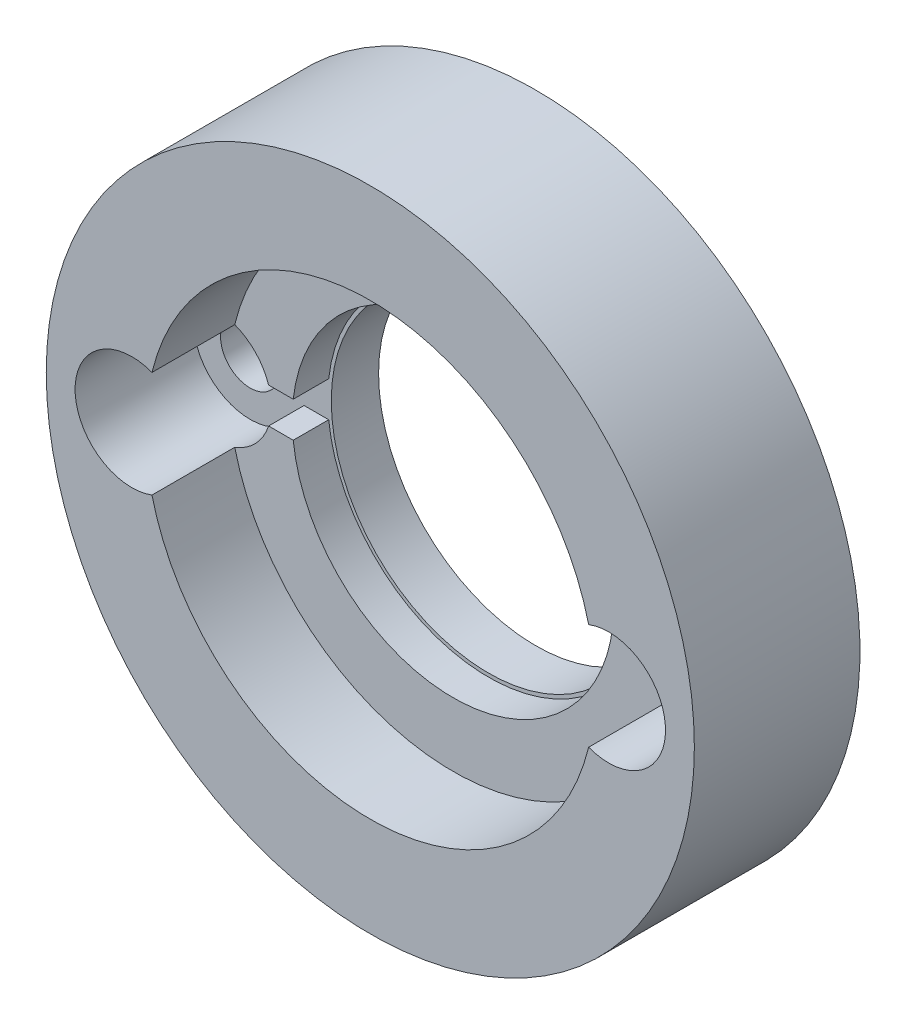
SolidWorks part; units mm, degrees
ref_plane "Alzado" through (0, 0, 0) normal (0, 0, 1) x (1, 0, 0)
ref_plane "Planta" through (0, 0, 0) normal (0, 1, 0) x (1, 0, 0)
ref_plane "Vista lateral" through (0, 0, 0) normal (1, 0, 0) x (0, 0, -1)
sketch "Croquis1" plane through (0, 0, 0) normal (0, 0, 1) x (1, 0, 0)
  line L0 (0, 8.3596) -> (0, -1.3417) construction
  line L1 (9, 0.75) -> (-9, 0.75)
  line L2 (0, 0.75) -> (0, -0.75)
  line L3 (9, -0.75) -> (-9, -0.75)
  line L4 (-9, 0.75) -> (-9, -0.75)
  line L5 (-12.48, 10.7299) -> (-12.48, -4.9079) construction
  line L6 (9, 0.75) -> (9, -0.75)
  line L7 (0, 0) -> (-17.6562, 0) construction
  circle A0 centre (-10.08, 0) radius 2.4
  circle A1 centre (-10.08, 0) radius 0.9
  circle A2 centre (10.08, 0) radius 0.9
  circle A3 centre (10.08, 0) radius 2.4
  circle A4 centre (0, 0) radius 13.7
  point P9 (0, 0)
  dimension "D1" = 1.8
  dimension "D4" = 4.8
  dimension "D6" = 27.4
  dimension "D2" = 1.5
  dimension "D3" = 9
  dimension "D5" = 12.48
extrude "Saliente-Extruir1" add sketch "Croquis1" along normal blind 5 contours A4 L1 A3 L3 A0
sketch "Croquis2" plane through (0, 0, 5) normal (0, 0, 1) x (1, 0, 0)
  circle A0 centre (0, 0) radius 9.5
  dimension "D1" = 19
extrude "Cortar-Extruir1" cut sketch "Croquis2" against normal blind 3.5
sketch "Croquis3" plane through (0, 0, 1.5) normal (0, 0, 1) x (1, 0, 0)
  circle A0 centre (0, 0) radius 6.8
  dimension "D1" = 13.6
extrude "Cortar-Extruir2" cut sketch "Croquis3" against normal blind 3
sketch "Croquis4" plane through (0, 0, 0) normal (0, 0, -1) x (-1, 0, 0)
  circle A0 centre (0, 0) radius 13.7 construction
  circle A1 centre (0, 0) radius 13.7
  circle A2 centre (0, 0) radius 6.65
  dimension "D1" = 13.3
extrude "Saliente-Extruir2" add sketch "Croquis4" along normal blind 2
sketch "Croquis5" plane through (0, 0, 5) normal (0, 0, 1) x (1, 0, 0)
  circle A0 centre (-10.08, 0) radius 1.25
  circle A1 centre (10.08, 0) radius 1.25
  dimension "D1" = 2.5
  dimension "D2" = 2.5
extrude "Cortar-Extruir3" cut sketch "Croquis5" against normal through all
